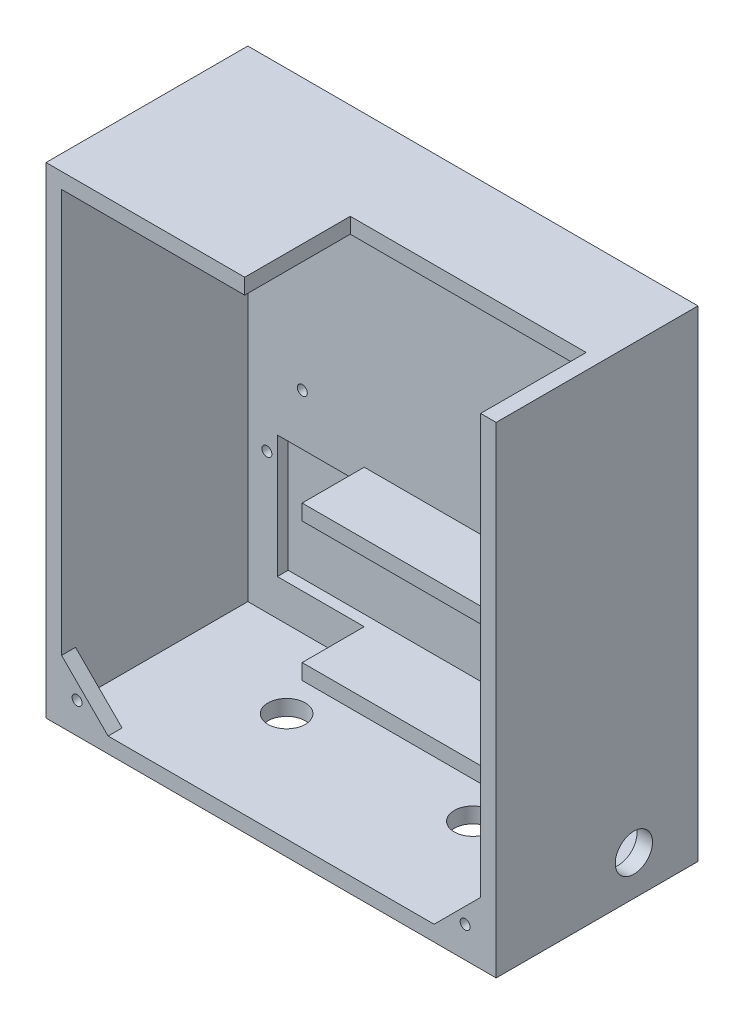
SolidWorks part; units mm, degrees
ref_plane "前视基准面" through (0, 0, 0) normal (0, 0, 1) x (1, 0, 0)
ref_plane "上视基准面" through (0, 0, 0) normal (0, 1, 0) x (1, 0, 0)
ref_plane "右视基准面" through (0, 0, 0) normal (1, 0, 0) x (0, 0, -1)
sketch "草图1" plane through (0, 0, 0) normal (0, 0, 1) x (1, 0, 0)
  line L0 (-86.7958, 0) -> (86.7958, 0) construction
  line L5 (-61.35, 61.5831) -> (-61.35, -61.3026) construction
  line L7 (0, 78.7449) -> (0, -70.7449) construction
  line L11 (61.35, 78.7522) -> (61.35, -70.7449) construction
  line L12 (-49.95, 40.9223) -> (-49.95, -27.6039) construction
  line L13 (-71.9776, 4) -> (71.9776, 4) construction
  line L14 (-61.6077, -23.5) -> (84.4481, -23.5) construction
  line L15 (62.35, 40.9223) -> (62.35, -37.6039) construction
  line L16 (-74.058, 31.5) -> (80.4255, 31.5) construction
  line L17 (-72.5, 58.75) -> (-72.5, -96.25)
  line L18 (-72.5, -96.25) -> (72.5, -96.25)
  line L19 (72.5, -96.25) -> (72.5, 58.75)
  line L20 (72.5, 58.75) -> (-72.5, 58.75)
  circle A2 centre (-61.35, 46.25) radius 1.6
  circle A3 centre (61.35, -46.6) radius 1.6
  circle A4 centre (61.35, 46.6) radius 1.6
  circle A7 centre (-61.35, -46.25) radius 1.6
  circle A16 centre (62.35, 31.5) radius 1.6
  circle A19 centre (62.35, -23.5) radius 1.6
  circle A22 centre (62.35, 31.5) radius 1.6
  circle A23 centre (62.35, -23.5) radius 1.6
  circle A32 centre (-49.95, 31.5) radius 1.6
  circle A34 centre (-49.95, 31.5) radius 1.6
  circle A35 centre (-49.95, -23.5) radius 1.6
  point P0 (0, 0)
  point P2 (0, 4)
  point P36 (0, -96.25)
  dimension "D4" = 61.35
  dimension "D3" = 46.25
  dimension "D5" = 3.2
  dimension "D6" = 3.2
  dimension "D9" = 46.6
  dimension "D10" = 3.2
  dimension "D11" = 3.2
  dimension "D14" = 3.2
  dimension "D18" = 3.2
  dimension "D19" = 3.2
  dimension "D7" = 46.6
  dimension "D8" = 46.25
  dimension "D22" = 3.2
  dimension "D23" = 112.3
  dimension "D13" = 15.1
  dimension "D12" = 155
  dimension "D15" = 27.5
  dimension "D16" = 27.5
  dimension "D17" = 1
  dimension "D20" = 145
  dimension "D21" = 61.35
extrude "凸台-拉伸1" add sketch "草图1" along normal blind 5
sketch "草图2" plane through (0, 0, 5) normal (0, 0, 1) x (1, 0, 0)
  line L0 (0, 18.9798) -> (0, -93.9798) construction
  line L1 (-30, -35) -> (30, -35)
  line L2 (-30, -35) -> (-30, -40)
  line L3 (-30, -40) -> (30, -40)
  line L4 (30, -35) -> (30, -40)
  line L5 (-30, -35) -> (30, -40) construction
  line L6 (-30, -40) -> (30, -35) construction
  line L7 (-30, -79.5) -> (30, -79.5)
  line L8 (-30, -79.5) -> (-30, -84.5)
  line L9 (-30, -84.5) -> (30, -84.5)
  line L10 (30, -79.5) -> (30, -84.5)
  line L11 (-30, -79.5) -> (30, -84.5) construction
  line L12 (-30, -84.5) -> (30, -79.5) construction
  line L13 (-30, -8.1096) -> (-30, -74.0695) construction
  point P0 (0, -37.5)
  point P5 (0, -82)
  dimension "D1" = 39.5
  dimension "D2" = 35
  dimension "D3" = 5
  dimension "D4" = 5
  dimension "D5" = 30
extrude "凸台-拉伸2" add sketch "草图2" along normal blind 20
sketch "草图3" plane through (0, 0, 5) normal (0, 0, 1) x (1, 0, 0)
  line L0 (-67.5, -91.25) -> (67.5, -91.25)
  line L1 (67.5, -91.25) -> (67.5, 53.75)
  line L3 (-67.5, 53.75) -> (-67.5, -91.25)
  line L4 (-72.5, -96.25) -> (72.5, -96.25)
  line L5 (72.5, -96.25) -> (72.5, 58.75)
  line L6 (72.5, 58.75) -> (-72.5, 58.75)
  line L7 (-72.5, 58.75) -> (-72.5, -96.25)
  line L8 (-67.5, 53.75) -> (67.5, 53.75)
  line L9 (-72.5, 58.75) -> (72.5, 58.75)
  point P3 (0, 58.75)
  line M12 (72.5, -96.25) -> (72.5, 58.75)
  line M13 (72.5, 58.75) -> (-72.5, 58.75)
  line M14 (-72.5, 58.75) -> (-72.5, -96.25)
  line M15 (-72.5, -96.25) -> (72.5, -96.25)
  dimension "D1" = 5
  dimension "D2" = 5
  dimension "D3" = 5
  dimension "D4" = 5
extrude "凸台-拉伸3" add sketch "草图3" along normal blind 60 contours L3 L1 L0 M13 M14 M15 M12
sketch "草图8" plane through (0, 0, 65) normal (0, 0, 1) x (1, 0, 0)
  line L0 (-67.5, -76.25) -> (-52.5, -91.25)
  line L1 (-67.5, 53.75) -> (-67.5, -91.25) construction
  line L2 (-67.5, -76.25) -> (-67.5, -91.25)
  line L3 (-67.5, -91.25) -> (-52.5, -91.25)
  line L4 (0, 84.5954) -> (0, -133.3642) construction
  line L5 (67.5, -91.25) -> (52.5, -91.25)
  line L6 (67.5, -76.25) -> (67.5, -91.25)
  line L7 (67.5, -76.25) -> (52.5, -91.25)
  circle A0 centre (-62.5, -86.25) radius 1.6
  circle A1 centre (62.5, -86.25) radius 1.6
  dimension "D5" = 3.2
  dimension "D1" = 15
  dimension "D2" = 15
  dimension "D3" = 5
  dimension "D4" = 5
extrude "凸台-拉伸7" add sketch "草图8" against normal blind 4.5
sketch "草图9" plane through (0, 53.75, 0) normal (0, -1, 0) x (1, 0, 0)
  line L0 (67.5, 31) -> (-8.5, 31)
  line L1 (67.5, 65) -> (67.5, 5) construction
  line L2 (-8.5, 31) -> (-8.5, 121)
  line L3 (-8.5, 121) -> (67.5, 121)
  line L4 (67.5, 121) -> (67.5, 31)
  line L5 (-67.5, 5) -> (67.5, 5) construction
  dimension "D1" = 26
  dimension "D2" = 90
  dimension "D3" = 76
extrude "切除-拉伸1" cut sketch "草图9" against normal blind 10
sketch "草图13" plane through (0, 0, 5) normal (0, 0, 1) x (1, 0, 0)
  line L0 (-30, -79.5) -> (-58, -79.5)
  line L1 (-58, -79.5) -> (-58, -40)
  line L2 (-58, -40) -> (58, -40)
  line L3 (58, -40) -> (58, -79.5)
  line L4 (58, -79.5) -> (-30, -79.5)
  line L5 (-30, -40) -> (30, -40) construction
  line L6 (0, -120.2134) -> (0, -13.1494) construction
  dimension "D1" = 116
  dimension "D2" = 58
extrude "切除-拉伸2" cut sketch "草图13" against normal blind 3.5
sketch "草图14" plane through (72.5, 0, 0) normal (1, 0, 0) x (0, 0, -1)
  circle A0 centre (-20.6431, -83.4628) radius 6
  dimension "D1" = 12
extrude "切除-拉伸3" cut sketch "草图14" against normal blind 10
sketch "草图15" plane through (0, -96.25, 0) normal (0, -1, 0) x (-1, 0, 0)
  line L0 (72.5, -65) -> (-72.5, -65) construction
  line L1 (72.5, 0) -> (-72.5, 0) construction
  line L2 (0, 11.155) -> (0, -79.3362) construction
  circle A0 centre (-30, -30) radius 6
  circle A1 centre (30, -30) radius 6
  point P2 (0, -65)
  dimension "D2" = 12
  dimension "D1" = 30
  dimension "D3" = 30
extrude "切除-拉伸4" cut sketch "草图15" against normal blind 10
